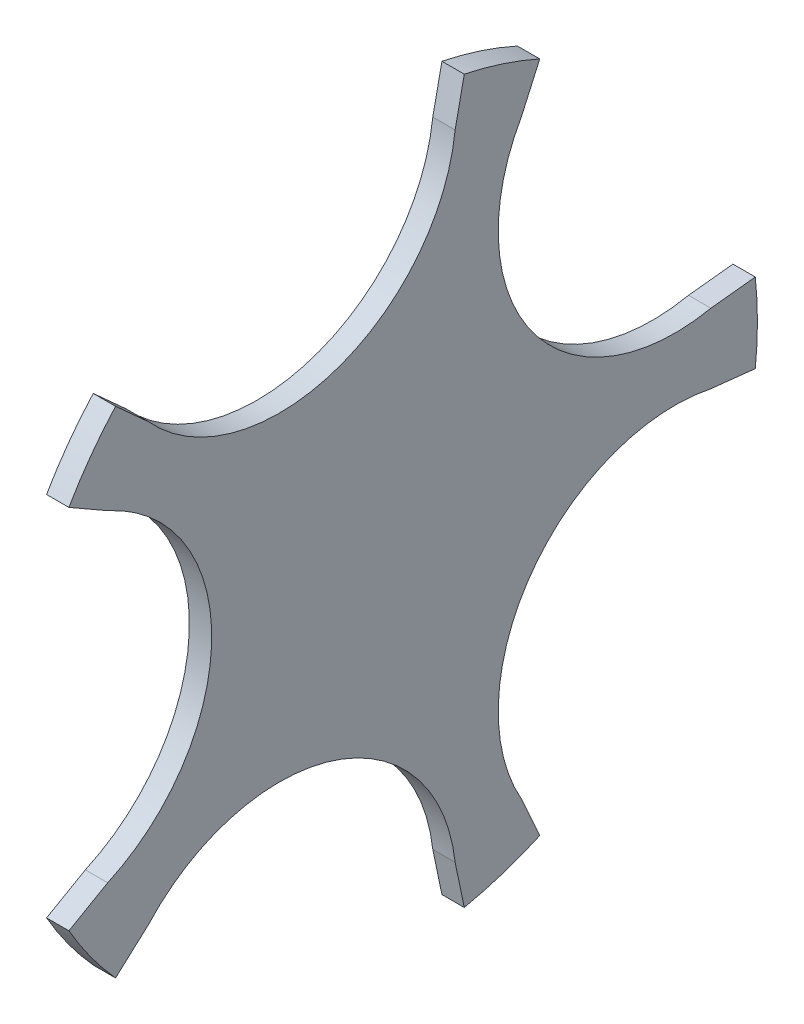
SolidWorks part; units mm, degrees
ref_plane "Piano frontale" through (0, 0, 0) normal (0, 0, 1) x (1, 0, 0)
ref_plane "Piano superiore" through (0, 0, 0) normal (0, 1, 0) x (1, 0, 0)
ref_plane "Piano destro" through (0, 0, 0) normal (1, 0, 0) x (0, 0, -1)
ref_plane "Piano1" through (7.6923, 0, 0) normal (1, 0, 0) x (0, 0, -1)
sketch "Schizzo1" plane through (7.6923, 0, 0) normal (1, 0, 0) x (0, 0, -1)
  line L0 (-6.1135, -5.5397) -> (-5.3726, -4.8684)
  line L1 (1.485, -7.0966) -> (1.6898, -8.0751)
  line L2 (3.3794, -7.5261) -> (2.9699, -6.6141)
  line L3 (7.2081, -0.7806) -> (8.202, -0.8883)
  line L4 (8.202, 0.8883) -> (7.2081, 0.7806)
  line L5 (2.9699, 6.6141) -> (3.3794, 7.5261)
  line L6 (1.6898, 8.0751) -> (1.485, 7.0966)
  line L7 (-5.3726, 4.8684) -> (-6.1135, 5.5397)
  line L8 (-7.1577, 4.1024) -> (-6.2903, 3.6053)
  line L9 (-6.2903, -3.6053) -> (-7.1577, -4.1024)
  arc A0 (-7.1577, -4.1024) -> (-6.1135, -5.5397) centre (0, 0) ccw
  arc A1 (-5.3726, -4.8684) -> (1.485, -7.0966) centre (-2.4465, -7.5295) cw
  arc A2 (1.6898, -8.0751) -> (3.3794, -7.5261) centre (0, 0) ccw
  arc A3 (2.9699, -6.6141) -> (7.2081, -0.7806) centre (6.405, -4.6535) cw
  arc A4 (8.202, -0.8883) -> (8.202, 0.8883) centre (0, 0) ccw
  arc A5 (7.2081, 0.7806) -> (2.9699, 6.6141) centre (6.405, 4.6535) cw
  arc A6 (3.3794, 7.5261) -> (1.6898, 8.0751) centre (0, 0) ccw
  arc A7 (1.485, 7.0966) -> (-5.3726, 4.8684) centre (-2.4465, 7.5295) cw
  arc A8 (-6.1135, 5.5397) -> (-7.1577, 4.1024) centre (0, 0) ccw
  arc A9 (-6.2903, 3.6053) -> (-6.2903, -3.6053) centre (-7.917, 0) cw
extrude "Estrusione-Estrusione1" add sketch "Schizzo1" against normal blind 0.5
